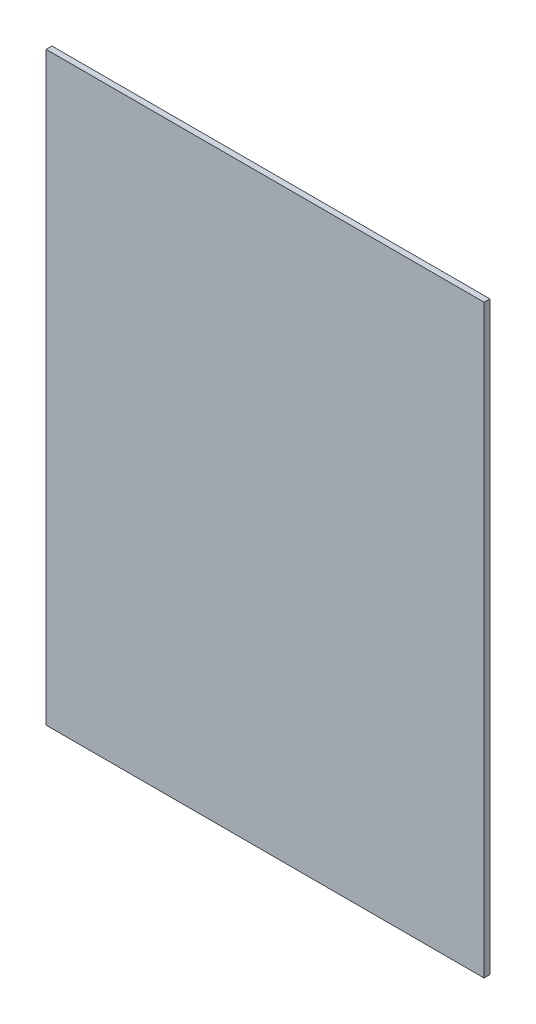
SolidWorks part; units mm, degrees
ref_plane "Front Plane" through (0, 0, 0) normal (0, 0, 1) x (1, 0, 0)
ref_plane "Top Plane" through (0, 0, 0) normal (0, 1, 0) x (1, 0, 0)
ref_plane "Right Plane" through (0, 0, 0) normal (1, 0, 0) x (0, 0, -1)
sketch "Sketch1" plane through (0, 0, 0) normal (0, 0, 1) x (1, 0, 0)
  line L1 (-75.05, 100.3) -> (75.05, 100.3)
  line L2 (-75.05, 100.3) -> (-75.05, -100.3)
  line L3 (-75.05, -100.3) -> (75.05, -100.3)
  line L4 (75.05, 100.3) -> (75.05, -100.3)
  line L5 (-75.05, 100.3) -> (75.05, -100.3) construction
  line L6 (-75.05, -100.3) -> (75.05, 100.3) construction
  point P0 (0, 0)
  dimension "D1" = 200.6
  dimension "D2" = 150.1
extrude "Boss-Extrude1" add sketch "Sketch1" along normal blind 2
